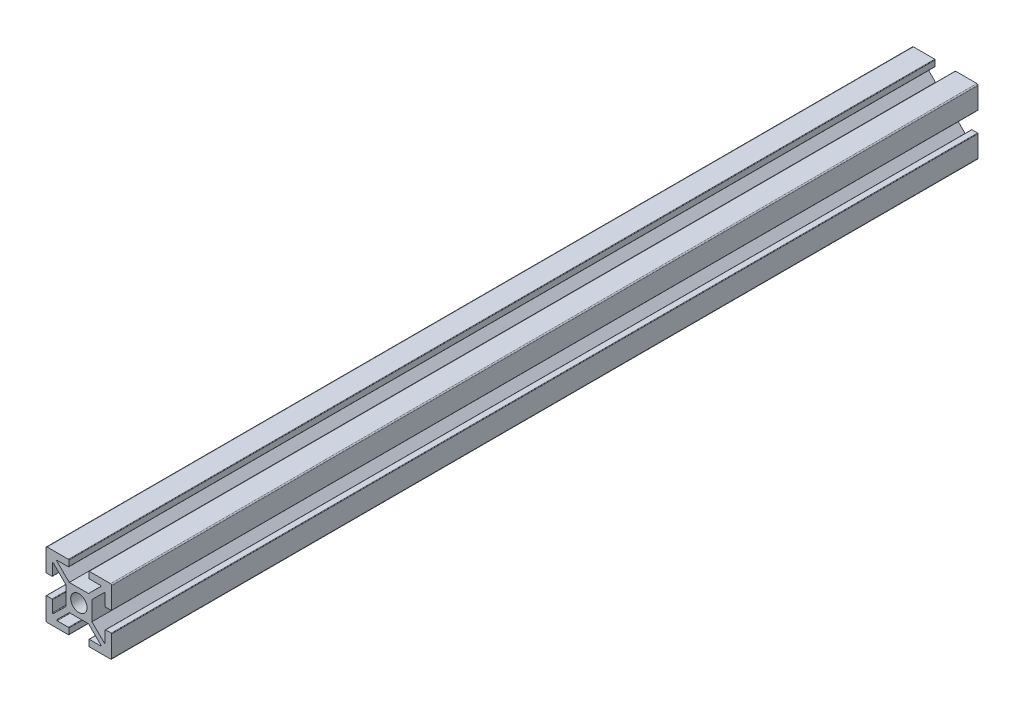
SolidWorks part; units mm, degrees
ref_plane "Front Plane" through (0, 0, 0) normal (0, 0, 1) x (1, 0, 0)
ref_plane "Top Plane" through (0, 0, 0) normal (0, 1, 0) x (1, 0, 0)
ref_plane "Right Plane" through (0, 0, 0) normal (1, 0, 0) x (0, 0, -1)
sketch "Sketch1" plane through (0, 0, 0) normal (0, 0, 1) x (1, 0, 0)
  line L0 (-31.3764, -0.0618) -> (-29.6764, -0.0618)
  line L1 (-24.6764, 6.9382) -> (-31.1764, 6.9382)
  line L2 (-31.5264, 0.0882) -> (-31.5264, 6.5882)
  line L3 (-18.5469, 0.9382) -> (-24.4133, 0.9382)
  line L4 (-25.4801, -6.0072) -> (-25.4801, -0.1164)
  line L5 (-29.5264, 0.0882) -> (-29.5264, 3.5244)
  line L6 (-28.0945, 4.9382) -> (-24.6764, 4.9382)
  line L7 (-24.5264, 5.0882) -> (-24.5264, 6.7882)
  line L8 (-29.5264, 4.9382) -> (-25.4801, 0.9382) construction
  line L9 (-29.271, 3.631) -> (-25.4801, -0.1164)
  line L10 (-28.1999, 4.6815) -> (-24.4133, 0.9382)
  line L11 (-13.4338, 4.9382) -> (-17.4801, 0.9382) construction
  line L12 (-21.4801, -3.0618) -> (-21.4801, 8.6268) construction
  line L13 (-21.4801, -3.0618) -> (-36.4642, -3.0618) construction
  line L14 (-14.7603, 4.6815) -> (-18.5469, 0.9382)
  line L15 (-13.6893, 3.631) -> (-17.4801, -0.1164)
  line L16 (-18.4338, 5.0882) -> (-18.4338, 6.7882)
  line L17 (-14.8657, 4.9382) -> (-18.2838, 4.9382)
  line L18 (-13.4338, 0.0882) -> (-13.4338, 3.5244)
  line L19 (-17.4801, -6.0072) -> (-17.4801, -0.1164)
  line L20 (-11.4338, 0.0882) -> (-11.4338, 6.5882)
  line L21 (-18.2838, 6.9382) -> (-11.7838, 6.9382)
  line L22 (-11.5838, -0.0618) -> (-13.2838, -0.0618)
  line L23 (-13.4338, -11.0618) -> (-17.4801, -7.0618) construction
  line L24 (-29.5264, -11.0618) -> (-25.4801, -7.0618) construction
  line L25 (-11.5838, -6.0618) -> (-13.2838, -6.0618)
  line L26 (-18.2838, -13.0618) -> (-11.7838, -13.0618)
  line L27 (-11.4338, -6.2118) -> (-11.4338, -12.7118)
  line L28 (-13.4338, -6.2118) -> (-13.4338, -9.648)
  line L29 (-14.8657, -11.0618) -> (-18.2838, -11.0618)
  line L30 (-18.4338, -11.2118) -> (-18.4338, -12.9118)
  line L31 (-13.6893, -9.7547) -> (-17.4801, -6.0072)
  line L32 (-14.7603, -10.8051) -> (-18.5469, -7.0618)
  line L33 (-28.1999, -10.8051) -> (-24.4133, -7.0618)
  line L34 (-29.271, -9.7547) -> (-25.4801, -6.0072)
  line L35 (-24.5264, -11.2118) -> (-24.5264, -12.9118)
  line L36 (-28.0945, -11.0618) -> (-24.6764, -11.0618)
  line L37 (-29.5264, -6.2118) -> (-29.5264, -9.648)
  line L38 (-18.5469, -7.0618) -> (-24.4133, -7.0618)
  line L39 (-31.5264, -6.2118) -> (-31.5264, -12.7118)
  line L40 (-24.6764, -13.0618) -> (-31.1764, -13.0618)
  line L41 (-31.3764, -6.0618) -> (-29.6764, -6.0618)
  circle A0 centre (-21.4801, -3.0618) radius 2.5
  arc A1 (-31.5264, 6.5882) -> (-31.1764, 6.9382) centre (-31.1764, 6.5882) cw
  arc A2 (-31.3764, -0.0618) -> (-31.5264, 0.0882) centre (-31.3764, 0.0882) cw
  arc A3 (-29.6764, -0.0618) -> (-29.5264, 0.0882) centre (-29.6764, 0.0882) ccw
  arc A4 (-24.6764, 6.9382) -> (-24.5264, 6.7882) centre (-24.6764, 6.7882) cw
  arc A5 (-24.6764, 4.9382) -> (-24.5264, 5.0882) centre (-24.6764, 5.0882) ccw
  arc A6 (-28.1999, 4.6815) -> (-28.0945, 4.9382) centre (-28.0945, 4.7882) cw
  arc A7 (-29.271, 3.631) -> (-29.5264, 3.5244) centre (-29.3764, 3.5244) ccw
  arc A8 (-13.6893, 3.631) -> (-13.4338, 3.5244) centre (-13.5838, 3.5244) cw
  arc A9 (-14.7603, 4.6815) -> (-14.8657, 4.9382) centre (-14.8657, 4.7882) ccw
  arc A10 (-18.2838, 4.9382) -> (-18.4338, 5.0882) centre (-18.2838, 5.0882) cw
  arc A11 (-18.2838, 6.9382) -> (-18.4338, 6.7882) centre (-18.2838, 6.7882) ccw
  arc A12 (-13.2838, -0.0618) -> (-13.4338, 0.0882) centre (-13.2838, 0.0882) cw
  arc A13 (-11.5838, -0.0618) -> (-11.4338, 0.0882) centre (-11.5838, 0.0882) ccw
  arc A14 (-11.4338, 6.5882) -> (-11.7838, 6.9382) centre (-11.7838, 6.5882) ccw
  arc A15 (-11.4338, -12.7118) -> (-11.7838, -13.0618) centre (-11.7838, -12.7118) cw
  arc A16 (-11.5838, -6.0618) -> (-11.4338, -6.2118) centre (-11.5838, -6.2118) cw
  arc A17 (-13.2838, -6.0618) -> (-13.4338, -6.2118) centre (-13.2838, -6.2118) ccw
  arc A18 (-18.2838, -13.0618) -> (-18.4338, -12.9118) centre (-18.2838, -12.9118) cw
  arc A19 (-18.2838, -11.0618) -> (-18.4338, -11.2118) centre (-18.2838, -11.2118) ccw
  arc A20 (-14.7603, -10.8051) -> (-14.8657, -11.0618) centre (-14.8657, -10.9118) cw
  arc A21 (-13.6893, -9.7547) -> (-13.4338, -9.648) centre (-13.5838, -9.648) ccw
  arc A22 (-29.271, -9.7547) -> (-29.5264, -9.648) centre (-29.3764, -9.648) cw
  arc A23 (-28.1999, -10.8051) -> (-28.0945, -11.0618) centre (-28.0945, -10.9118) ccw
  arc A24 (-24.6764, -11.0618) -> (-24.5264, -11.2118) centre (-24.6764, -11.2118) cw
  arc A25 (-24.6764, -13.0618) -> (-24.5264, -12.9118) centre (-24.6764, -12.9118) ccw
  arc A26 (-29.6764, -6.0618) -> (-29.5264, -6.2118) centre (-29.6764, -6.2118) cw
  arc A27 (-31.3764, -6.0618) -> (-31.5264, -6.2118) centre (-31.3764, -6.2118) ccw
  arc A28 (-31.5264, -12.7118) -> (-31.1764, -13.0618) centre (-31.1764, -12.7118) ccw
  point P27 (-18.4338, 4.9382)
  point P28 (-11.4338, -13.0618)
  point P47 (-17.4801, -3.0618)
  point P57 (-21.4801, 0.9382)
  point P59 (-18.4338, 6.9382)
  point P60 (-13.4338, -0.0618)
  point P61 (-11.4338, -0.0618)
  point P62 (-11.4338, 6.9382)
  point P112 (-25.4801, -3.0618)
  point P113 (-11.4338, -6.0618)
  point P114 (-13.4338, -6.0618)
  point P115 (-18.4338, -13.0618)
  point P116 (-21.4801, -7.0618)
  point P117 (-24.5264, -11.0618)
  point P118 (-24.5264, -13.0618)
  point P119 (-29.5264, -6.0618)
  point P120 (-18.4338, -11.0618)
  point P121 (-31.5264, -6.0618)
  point P122 (-31.5264, -13.0618)
  dimension "D3" = 0.35
  dimension "D4" = 0.15
  dimension "D5" = 0.15
  dimension "D6" = 0.15
  dimension "D7" = 0.15
  dimension "D8" = 0.15
  dimension "D9" = 0.15
  dimension "D1" = 0.75
  dimension "D2" = 0.75
extrude "Boss-Extrude1" add sketch "Sketch1" along normal blind 264.91
